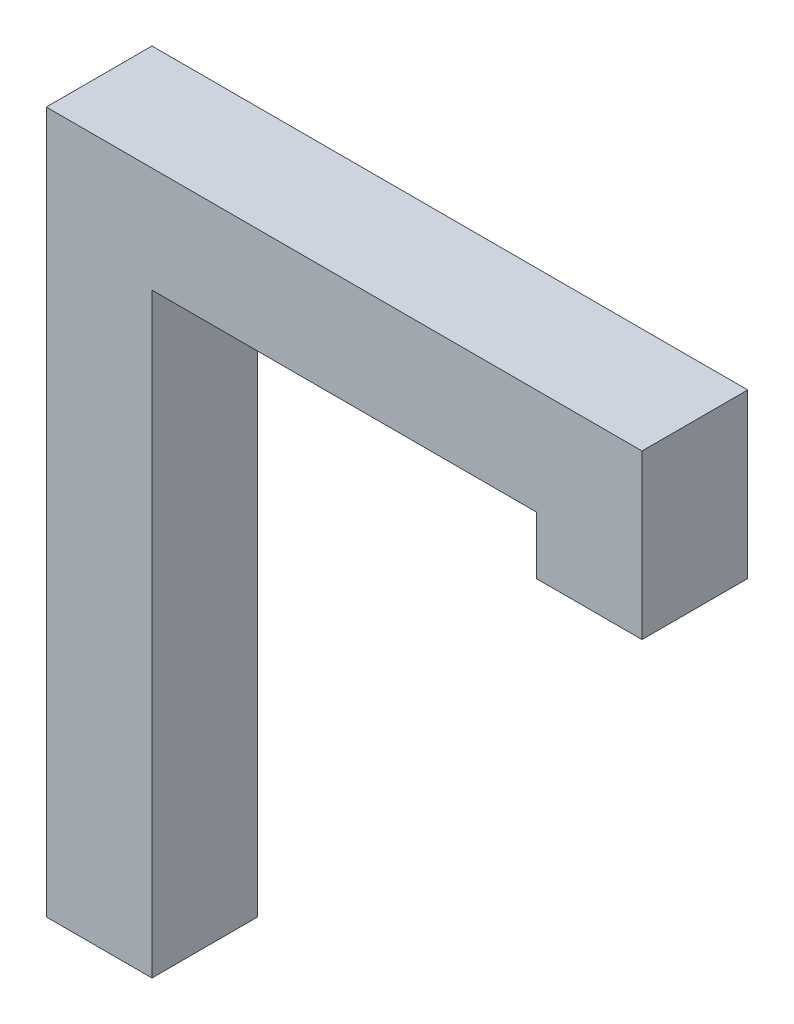
SolidWorks part; units mm, degrees
material "ﾁｰｸ材"
ref_plane "正面" through (0, 0, 0) normal (0, 0, 1) x (1, 0, 0)
ref_plane "平面" through (0, 0, 0) normal (0, 1, 0) x (1, 0, 0)
ref_plane "右側面" through (0, 0, 0) normal (1, 0, 0) x (0, 0, -1)
sketch "ｽｹｯﾁ1" plane through (0, 0, 0) normal (0, 0, 1) x (1, 0, 0)
  line L0 (0, 0) -> (-5.5, 0)
  line L1 (-5.5, 0) -> (-5.5, 36.5)
  line L2 (-5.5, 36.5) -> (25.5, 36.5)
  line L3 (25.5, 36.5) -> (25.5, 28)
  line L4 (25.5, 28) -> (20, 28)
  line L5 (20, 28) -> (20, 31)
  line L6 (20, 31) -> (0, 31)
  line L7 (0, 31) -> (0, 0)
  dimension "D1" = 5.5
  dimension "D2" = 31
  dimension "D3" = 5.5
  dimension "D4" = 20
  dimension "D5" = 3
  dimension "D6" = 5.5
extrude "ﾎﾞｽ - 押し出し1" add sketch "ｽｹｯﾁ1" along normal blind 5.5
